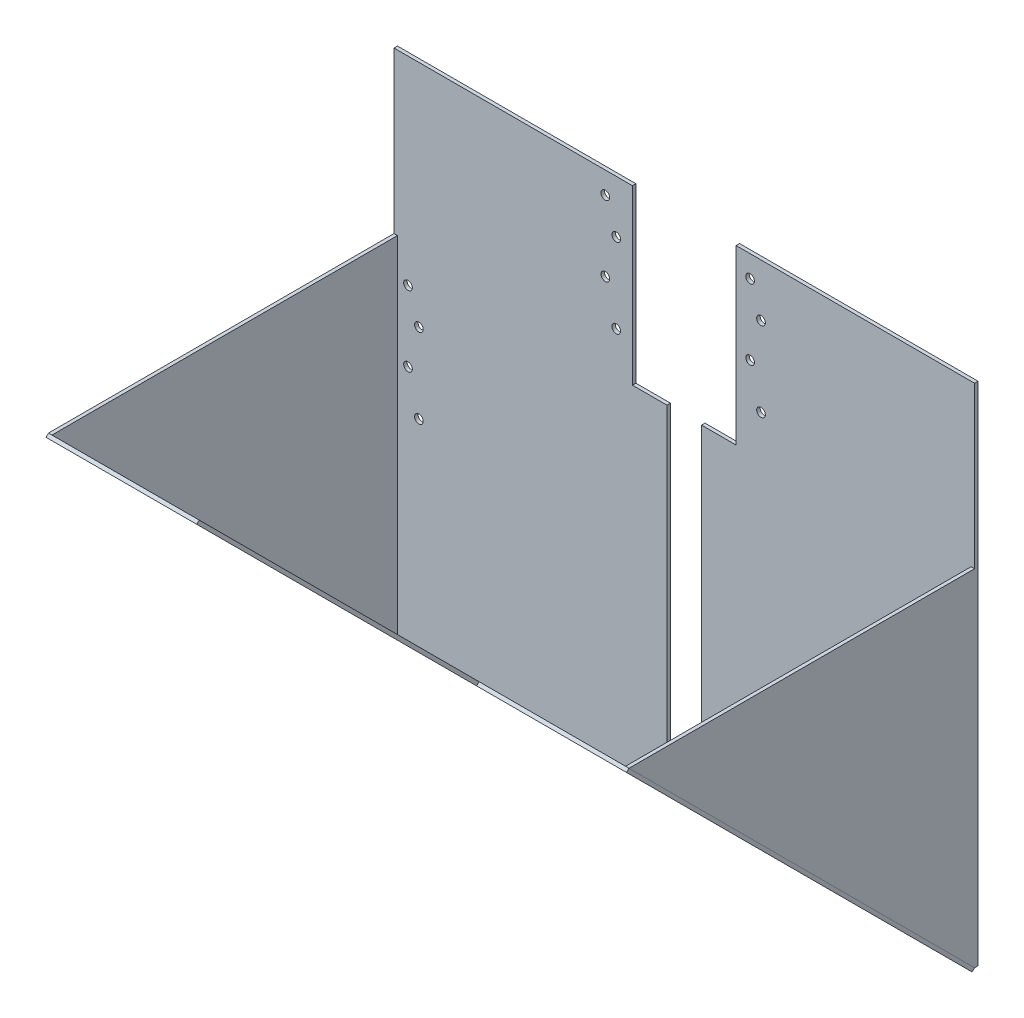
SolidWorks part; units mm, degrees
material "6061 合金"
ref_plane "前视基准面" through (0, 0, 0) normal (0, 0, 1) x (1, 0, 0)
ref_plane "上视基准面" through (0, 0, 0) normal (0, 1, 0) x (1, 0, 0)
ref_plane "右视基准面" through (0, 0, 0) normal (1, 0, 0) x (0, 0, -1)
sketch "草图1" plane through (0, 0, 0) normal (0, 0, 1) x (1, 0, 0)
  line L1 (2433.8557, 2029.7037) -> (2433.8557, 1836.7037)
  line L2 (2413.8557, 2129.7037) -> (2413.8557, 2029.7037)
  line L3 (2413.8557, 2029.7037) -> (2433.8557, 2029.7037)
  line L4 (2433.8557, 1836.7037) -> (2275.8557, 1836.7037)
  line L5 (2473.8557, 2129.7037) -> (2473.8557, 2029.7037)
  line L6 (2473.8557, 2029.7037) -> (2453.8557, 2029.7037)
  line L7 (2453.8557, 2029.7037) -> (2453.8557, 1836.7037)
  line L8 (2453.8557, 1836.7037) -> (2611.8557, 1836.7037)
  line L12 (2275.8557, 2129.7037) -> (2413.8557, 2129.7037)
  line L17 (2611.8557, 2129.7037) -> (2473.8557, 2129.7037)
  line L18 (2275.8557, 2129.7037) -> (2275.8557, 1836.7037)
  line L26 (2611.8557, 2129.7037) -> (2611.8557, 1836.7037)
  circle A0 centre (2404.4759, 2099.3037) radius 2.5
  circle A1 centre (2404.4759, 2053.2834) radius 2.5
  circle A2 centre (2398.1557, 2076.3037) radius 2.5
  circle A3 centre (2398.1557, 2117.1037) radius 2.5
  circle A12 centre (2488.2759, 2099.3037) radius 2.5
  circle A13 centre (2488.2759, 2053.2834) radius 2.5
  circle A14 centre (2481.9557, 2076.3037) radius 2.5
  circle A15 centre (2481.9557, 2117.1037) radius 2.5
  circle A16 centre (2290.2759, 1997.0037) radius 2.5
  circle A17 centre (2290.2759, 1950.9834) radius 2.5
  circle A18 centre (2283.9557, 1974.0037) radius 2.5
  circle A19 centre (2283.9557, 2014.8037) radius 2.5
  circle A20 centre (2602.4759, 1997.0037) radius 2.5
  circle A21 centre (2602.4759, 1950.9834) radius 2.5
  circle A22 centre (2596.1557, 1974.0037) radius 2.5
  circle A23 centre (2596.1557, 2014.8037) radius 2.5
extrude "凸台-拉伸2" add sketch "草图1" along normal blind 2
sketch "草图5" plane through (2611.8557, 0, 0) normal (1, 0, 0) x (0, 0, -1)
  line L0 (-2, 1836.7037) -> (-2, 2036.7037)
  line L1 (-2, 1836.7037) -> (-2, 2129.7037) construction
  line L2 (-2, 2036.7037) -> (-202, 2036.7037)
  line L3 (-202, 2036.7037) -> (-2, 1836.7037)
extrude "凸台-拉伸5" add sketch "草图5" against normal blind 2
sketch "草图6" plane through (2275.8557, 0, 0) normal (-1, 0, 0) x (0, 0, 1)
  line L0 (2, 1836.7037) -> (2, 2036.7037)
  line L1 (2, 2129.7037) -> (2, 1836.7037) construction
  line L2 (2, 2036.7037) -> (202, 2036.7037)
  line L3 (202, 2036.7037) -> (2, 1836.7037)
extrude "凸台-拉伸6" add sketch "草图6" against normal blind 2
sketch "草图7" plane through (0, 917.3518, -917.3518) normal (0, -0.7071, 0.7071) x (1, 0, 0)
  line L3 (2277.8557, 1300.1598) -> (2433.8557, 1300.1598) construction
  line L5 (2417.8557, 1300.1598) -> (2417.8557, 1350.1598)
  line L6 (2417.8557, 1350.1598) -> (2362.8557, 1582.6575)
  line L10 (2453.8557, 1300.1598) -> (2609.8557, 1300.1598) construction
  line L11 (2469.8557, 1300.1598) -> (2469.8557, 1350.1598)
  line L13 (2524.8557, 1582.6575) -> (2469.8557, 1350.1598)
  line L14 (2275.8557, 1300.1598) -> (2275.8557, 1583.0025)
  line L15 (2275.8557, 1583.0025) -> (2362.8557, 1582.6575)
  line L16 (2275.8557, 1300.1598) -> (2417.8557, 1300.1598)
  line L17 (2611.8557, 1583.0025) -> (2611.8557, 1300.1598)
  line L18 (2469.8557, 1300.1598) -> (2611.8557, 1300.1598)
  line L19 (2524.8557, 1582.6575) -> (2611.8557, 1583.0025)
extrude "凸台-拉伸7" add sketch "草图7" along normal blind 2 separate body
